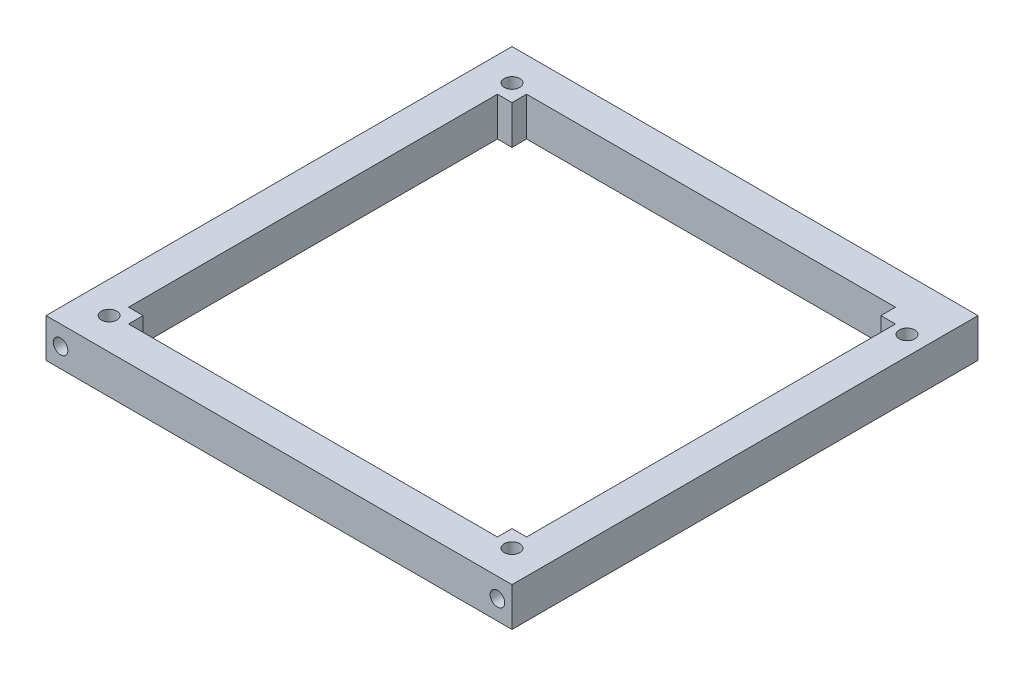
SolidWorks part; units mm, degrees
material "Aluminum"
ref_plane "Front Plane" through (0, 0, 0) normal (0, 0, 1) x (1, 0, 0)
ref_plane "Top Plane" through (0, 0, 0) normal (0, 1, 0) x (1, 0, 0)
ref_plane "Right Plane" through (0, 0, 0) normal (1, 0, 0) x (0, 0, -1)
sketch "Sketch1" plane through (0, 0, 0) normal (0, 1, 0) x (1, 0, 0)
  line L1 (48, -48) -> (-48, -48)
  line L2 (48, -48) -> (48, 48)
  line L3 (48, 48) -> (-48, 48)
  line L4 (-48, -48) -> (-48, 48)
  line L5 (48, -48) -> (-48, 48) construction
  line L6 (48, 48) -> (-48, -48) construction
  line L7 (40, -40) -> (-40, -40)
  line L8 (40, -40) -> (40, 40)
  line L9 (40, 40) -> (-40, 40)
  line L10 (-40, -40) -> (-40, 40)
  line L11 (40, -40) -> (-40, 40) construction
  line L12 (40, 40) -> (-40, -40) construction
  point P0 (0, 0)
  point P6 (0, 0)
  dimension "D1" = 96
  dimension "D2" = 96
  dimension "D3" = 8
extrude "Boss-Extrude1" add sketch "Sketch1" along normal blind 8
hole_wizard "Ø3.0 (3) Diameter Hole6" positions "Sketch8" profile "Sketch7" hole size "Ø3.0" standard "ANSI Metric"
sketch "Sketch8" plane through (0, 0, 48) normal (0, 0, 1) x (1, 0, 0)
  line L1 (48, 8) -> (48, 0) construction
  line L2 (-48, 8) -> (48, 8) construction
  line L3 (-48, 8) -> (-48, 0) construction
  point P0 (45, 4)
  point P10 (-45, 4)
  dimension "D1" = 4
  dimension "D2" = 3
  dimension "D3" = 4
  dimension "D4" = 3
sketch "Sketch7" plane through (45, 4, 48) normal (1, 0, 0) x (0, -1, 0)
  line L0 (0, 0) -> (0, 6)
  line L1 (0, 6) -> (1.5, 6)
  line L2 (1.5, 6) -> (1.5, 0)
  line L5 (1.5, 0) -> (0, 0)
  line L10 (0, 6) -> (-1.5, 6) construction
  line L11 (0, -6.35) -> (0, 107.95) construction
  dimension "Hole Dia." = 3
  dimension "Hole Depth" = 6
  dimension "Drill Angle" = 180
hole_wizard "Ø3.0 (3) Diameter Hole3" positions "Sketch10" profile "Sketch9" hole size "Ø3.0" standard "ANSI Metric"
sketch "Sketch10" plane through (0, 0, -48) normal (0, 0, -1) x (-1, 0, 0)
  line L0 (48, 8) -> (48, 0) construction
  line L2 (-48, 8) -> (-48, 0) construction
  line L4 (-48, 8) -> (48, 8) construction
  point P2 (45, 4)
  point P8 (-45, 4)
  dimension "D1" = 3
  dimension "D2" = 4
  dimension "D3" = 4
  dimension "D4" = 3
sketch "Sketch9" plane through (-45, 4, -48) normal (1, 0, 0) x (0, 1, 0)
  line L0 (0, 0) -> (0, 6)
  line L1 (0, 6) -> (1.5, 6)
  line L2 (1.5, 6) -> (1.5, 0)
  line L5 (1.5, 0) -> (0, 0)
  line L10 (0, 6) -> (-1.5, 6) construction
  line L11 (0, -6.35) -> (0, 107.95) construction
  dimension "Hole Dia." = 3
  dimension "Hole Depth" = 6
  dimension "Drill Angle" = 180
sketch "Sketch27" plane through (0, 8, 0) normal (0, 1, 0) x (1, 0, 0)
  line L0 (-40, 40) -> (-40, -40) construction
  line L1 (41, -41) -> (-41, -41)
  line L2 (41, -41) -> (41, 41)
  line L3 (41, 41) -> (-41, 41)
  line L4 (-41, -41) -> (-41, 41)
  line L5 (41, -41) -> (-41, 41) construction
  line L6 (41, 41) -> (-41, -41) construction
  line L7 (40, 40) -> (-40, 40) construction
  point P0 (0, 0)
  dimension "D1" = 1
  dimension "D2" = 1
extrude "Cut-Extrude2" cut sketch "Sketch27" against normal blind 10
sketch "Sketch35" plane through (0, 8, 0) normal (0, 1, 0) x (1, 0, 0)
  line L0 (0, 0) -> (0, 22.3578) construction
  line L1 (-41, 41) -> (-38, 41)
  line L2 (-41, 41) -> (-41, 38)
  line L3 (-41, 38) -> (-38, 38)
  line L4 (-38, 41) -> (-38, 38)
  line L5 (0, 0) -> (17.564, 0) construction
  line L6 (38, 41) -> (38, 38)
  line L7 (41, 38) -> (38, 38)
  line L8 (41, 41) -> (41, 38)
  line L9 (41, 41) -> (38, 41)
  line L10 (41, -41) -> (38, -41)
  line L11 (41, -41) -> (41, -38)
  line L12 (41, -38) -> (38, -38)
  line L13 (38, -41) -> (38, -38)
  line L14 (-38, -41) -> (-38, -38)
  line L15 (-41, -38) -> (-38, -38)
  line L16 (-41, -41) -> (-41, -38)
  line L17 (-41, -41) -> (-38, -41)
  dimension "D1" = 3
  dimension "D2" = 3
extrude "Boss-Extrude2" add sketch "Sketch35" against normal blind 8
hole_wizard "Ø3.2 (3.2) Diameter Hole1" positions "Sketch40" profile "Sketch39" hole size "Ø3.2" standard "ANSI Metric" end condition through all
sketch "Sketch40" plane through (0, 8, 0) normal (0, 1, 0) x (1, 0, 0)
  line L19 (0, 0) -> (0, 66.647) construction
  line L22 (0, 0) -> (93.7022, 0) construction
  point P57 (44.05, 37.33)
  point P58 (41.5, -41.5)
  point P88 (-41.5, -41.5)
  point P97 (-41.5, 41.5)
  dimension "D1" = 41.5
  dimension "D2" = 44.05
  dimension "D5" = 41.5
  dimension "D6" = 41.5
  dimension "D7" = 41.5
  dimension "D8" = 41.5
  dimension "D9" = 37.33
  dimension "D10" = 41.5
sketch "Sketch39" plane through (44.05, 8, -37.33) normal (1, 0, 0) x (0, 0, 1)
  line L0 (0, 0) -> (0, 8)
  line L1 (0, 8) -> (1.6, 8)
  line L2 (1.6, 8) -> (1.6, 0)
  line L5 (1.6, 0) -> (0, 0)
  line L11 (0, -6.35) -> (0, 107.95) construction
  dimension "Thru Hole Dia." = 3.2
  dimension "Thru Hole Depth" = 8
